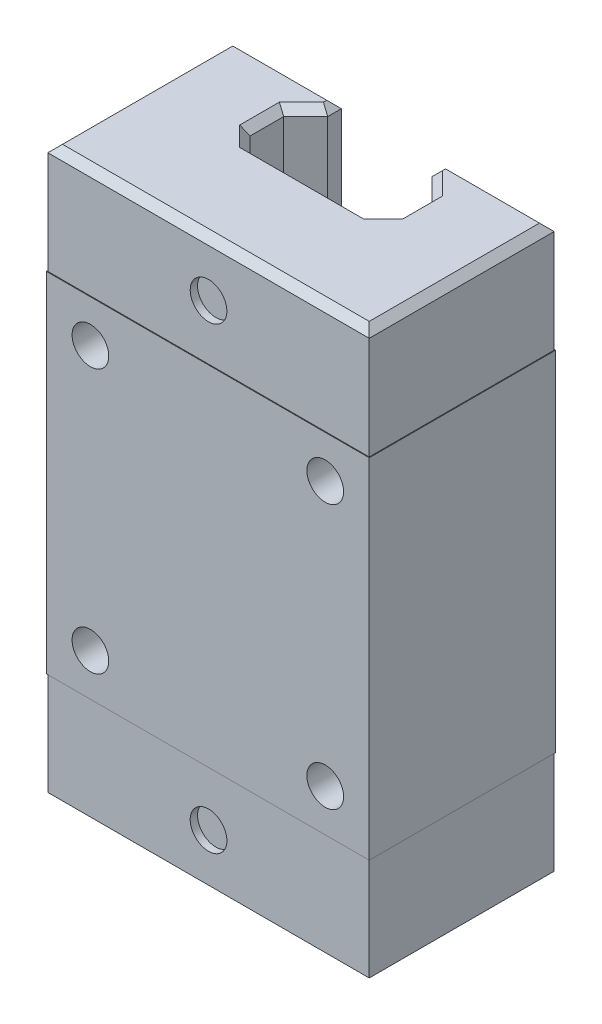
SolidWorks part; units mm, degrees
ref_plane "前视基准面" through (0, 0, 0) normal (0, 0, 1) x (1, 0, 0)
ref_plane "上视基准面" through (0, 0, 0) normal (0, 1, 0) x (1, 0, 0)
ref_plane "右视基准面" through (0, 0, 0) normal (1, 0, 0) x (0, 0, -1)
other "Configuration Table"
sketch "草图1" plane through (0, 0, 0) normal (0, 1, 0) x (1, 0, 0)
  line L1 (-22, 12.7) -> (22, 12.7)
  line L2 (-22, 12.7) -> (-22, -12.7)
  line L3 (-22, -12.7) -> (22, -12.7)
  line L4 (22, 12.7) -> (22, -12.7)
  line L5 (-22, 12.7) -> (22, -12.7) construction
  line L6 (-22, -12.7) -> (22, 12.7) construction
  point P0 (0, 0)
  dimension "D1" = 44
  dimension "D2" = 25.4
extrude "凸台-拉伸1" add sketch "草图1" along normal blind 77.5
sketch "草图2" plane through (0, 0, 0) normal (0, -1, 0) x (1, 0, 0)
  line L1 (-8, -1.2) -> (8, -1.2)
  line L2 (-10, -3.2) -> (-10, -18.7)
  line L3 (-10, -18.7) -> (10, -18.7)
  line L4 (10, -3.2) -> (10, -18.7)
  line L5 (-10, -3.2) -> (-8, -1.2)
  line L6 (8, -1.2) -> (10, -3.2)
  line L7 (10, -7.7) -> (7, -10.7)
  line L8 (7, -10.7) -> (7, -14.7)
  line L9 (7, -14.7) -> (10, -17.7)
  line L10 (0, 0) -> (0, 6.8091) construction
  line L11 (-7, -14.7) -> (-10, -17.7)
  line L12 (-7, -10.7) -> (-7, -14.7)
  line L13 (-10, -7.7) -> (-7, -10.7)
  line L14 (22, -12.7) -> (-22, -12.7) construction
  point P0 (-10, -1.2)
  point P3 (10, -1.2)
  point P10 (0, -1.2)
  point P20 (7, -12.7)
  line M14 (-22, -12.7) -> (22, -12.7)
  dimension "D1" = 17.5
  dimension "D2" = 20
  dimension "D3" = 1
  dimension "D6" = 4
  dimension "D7" = 10
  dimension "D8" = 45
  dimension "D9" = 45
extrude "切除-拉伸1" cut sketch "草图2" against normal through all contours L2 L13 L12 L8 L7 L4 L6 L1 L5 M14
sketch "草图3" plane through (0, 0, 12.7) normal (0, 0, 1) x (1, 0, 0)
  line L0 (0, 0) -> (0, 11.1114) construction
  line L1 (22, 38.75) -> (5.064, 38.75) construction
  line L2 (22, 77.5) -> (22, 0) construction
  circle A0 centre (-16, 20.75) radius 2.5
  circle A1 centre (-16, 56.75) radius 2.5
  circle A2 centre (16, 56.75) radius 2.5
  circle A3 centre (16, 20.75) radius 2.5
  dimension "D1" = 5
  dimension "D2" = 36
  dimension "D3" = 16
extrude "切除-拉伸2" cut sketch "草图3" against normal blind 6
sketch "草图4" plane through (0, 77.5, 0) normal (0, 1, 0) x (1, 0, 0)
  line L0 (21.9, 12.6) -> (7.1, 12.6)
  line L1 (7.1, 12.6) -> (7.1, 10.7414)
  line L2 (7.1, 10.7414) -> (10.1, 7.7414)
  line L3 (10.1, 7.7414) -> (10.1, 3.1586)
  line L4 (10.1, 3.1586) -> (8.0414, 1.1)
  line L5 (8.0414, 1.1) -> (-8.0414, 1.1)
  line L6 (-8.0414, 1.1) -> (-10.1, 3.1586)
  line L7 (-10.1, 3.1586) -> (-10.1, 7.7414)
  line L8 (-10.1, 7.7414) -> (-7.1, 10.7414)
  line L9 (-7.1, 10.7414) -> (-7.1, 12.6)
  line L10 (-7.1, 12.6) -> (-21.9, 12.6)
  line L11 (-21.9, 12.6) -> (-21.9, -12.6)
  line L12 (-21.9, -12.6) -> (21.9, -12.6)
  line L13 (21.9, -12.6) -> (21.9, 12.6)
  line L14 (22, 12.7) -> (7, 12.7)
  line L15 (7, 12.7) -> (7, 10.7)
  line L16 (7, 10.7) -> (10, 7.7)
  line L17 (10, 7.7) -> (10, 3.2)
  line L18 (10, 3.2) -> (8, 1.2)
  line L19 (8, 1.2) -> (-8, 1.2)
  line L20 (-8, 1.2) -> (-10, 3.2)
  line L21 (-10, 3.2) -> (-10, 7.7)
  line L22 (-10, 7.7) -> (-7, 10.7)
  line L23 (-7, 10.7) -> (-7, 12.7)
  line L24 (-7, 12.7) -> (-22, 12.7)
  line L25 (-22, 12.7) -> (-22, -12.7)
  line L26 (-22, -12.7) -> (22, -12.7)
  line L27 (22, -12.7) -> (22, 12.7)
  line L28 (22, 12.7) -> (7, 12.7)
  line L29 (7, 12.7) -> (7, 10.7)
  line L30 (7, 10.7) -> (10, 7.7)
  line L31 (10, 7.7) -> (10, 3.2)
  line L32 (10, 3.2) -> (8, 1.2)
  line L33 (8, 1.2) -> (-8, 1.2)
  line L34 (-8, 1.2) -> (-10, 3.2)
  line L35 (-10, 3.2) -> (-10, 7.7)
  line L36 (-10, 7.7) -> (-7, 10.7)
  line L37 (-7, 10.7) -> (-7, 12.7)
  line L38 (-7, 12.7) -> (-22, 12.7)
  line L39 (-22, 12.7) -> (-22, -12.7)
  line L40 (-22, -12.7) -> (22, -12.7)
  line L41 (22, -12.7) -> (22, 12.7)
  line M29 (22, 12.7) -> (7, 12.7)
  line M30 (7, 12.7) -> (7, 10.7)
  line M31 (7, 10.7) -> (10, 7.7)
  line M32 (10, 7.7) -> (10, 3.2)
  line M33 (10, 3.2) -> (8, 1.2)
  line M34 (8, 1.2) -> (-8, 1.2)
  line M35 (-8, 1.2) -> (-10, 3.2)
  line M36 (-10, 3.2) -> (-10, 7.7)
  line M37 (-10, 7.7) -> (-7, 10.7)
  line M38 (-7, 10.7) -> (-7, 12.7)
  line M39 (-7, 12.7) -> (-22, 12.7)
  line M40 (-22, 12.7) -> (-22, -12.7)
  line M41 (-22, -12.7) -> (22, -12.7)
  line M42 (22, -12.7) -> (22, 12.7)
  dimension "D1" = 0
  dimension "D2" = 0.1
extrude "切除-拉伸3" cut sketch "草图4" against normal blind 15 contours L13 L12 L11 L10 L9 L8 L7 L6 L5 L4 L3 L2 L1 L0 M42 M29 M30 M31 M32 M33 M34 M35 M36 M37 M38 M39 M40 M41
ref_plane "基准面1" through (0, 38.75, 0) normal (0, 1, 0) x (1, 0, 0)
mirror "镜向1" about plane through (0, 38.75, 0) normal (0, 1, 0) of "切除-拉伸3"
sketch "草图5" plane through (0, 0, 12.6) normal (0, 0, 1) x (1, 0, 0)
  line L0 (-22, 38.75) -> (-8.0577, 38.75) construction
  line L1 (-22, 62.5) -> (-22, 15) construction
  line L2 (13.97, 38.75) -> (-13.97, 38.75) construction
  circle A0 centre (0, 7.5) radius 2.5
  circle A1 centre (0, 70) radius 2.5
  dimension "D1" = 5
  dimension "D2" = 7.5
extrude "切除-拉伸4" cut sketch "草图5" against normal blind 1
chamfer "倒角1" distance 1 angle 45 28 edges at (7.1, 0, -11.6707) (8.6, 0, -9.2414) (10.1, 0, -5.45) (9.0707, 0, -2.1293) (0, 0, -1.1) (-9.0707, 0, -2.1293) (-10.1, 0, -5.45) (-8.6, 0, -9.2414) (-7.1, 0, -11.6707) (-14.5, 0, -12.6) (-21.9, 0, 0) (0, 0, 12.6) (21.9, 0, 0) (14.5, 0, -12.6) (-21.9, 77.5, 0) (-14.5, 77.5, -12.6) (-7.1, 77.5, -11.6707) (-8.6, 77.5, -9.2414) (-10.1, 77.5, -5.45) (-9.0707, 77.5, -2.1293) (0, 77.5, -1.1) (9.0707, 77.5, -2.1293) (10.1, 77.5, -5.45) (8.6, 77.5, -9.2414) (7.1, 77.5, -11.6707) (14.5, 77.5, -12.6) (21.9, 77.5, 0) (0, 77.5, 12.6)
